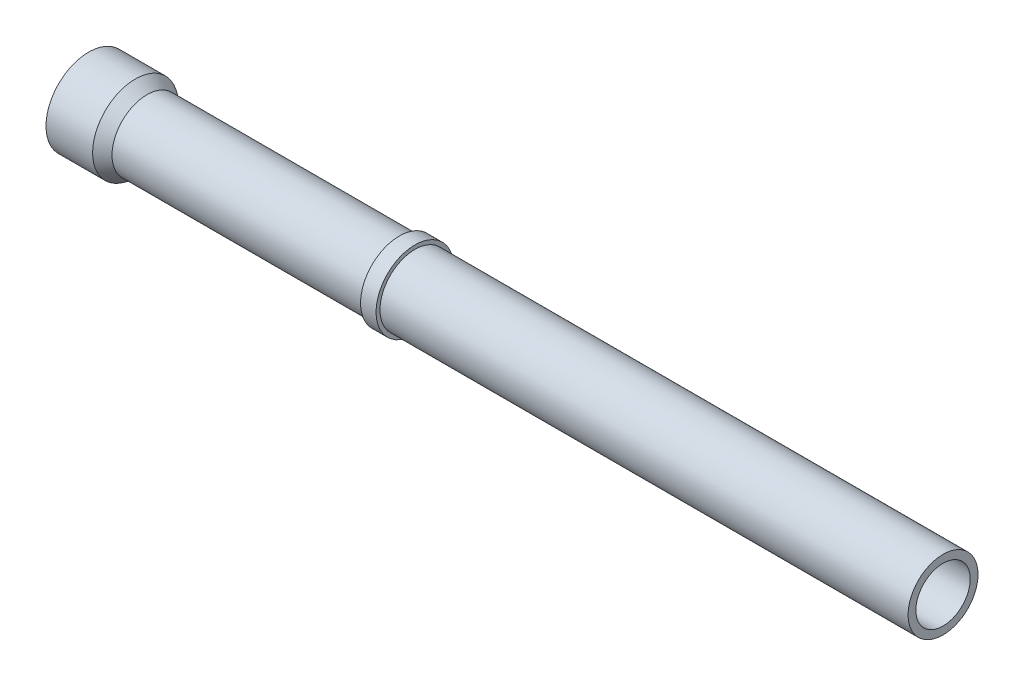
SolidWorks part; units mm, degrees
ref_plane "Front Plane" through (0, 0, 0) normal (0, 0, 1) x (1, 0, 0)
ref_plane "Top Plane" through (0, 0, 0) normal (0, 1, 0) x (1, 0, 0)
ref_plane "Right Plane" through (0, 0, 0) normal (1, 0, 0) x (0, 0, -1)
sketch "Sketch1" plane through (0, 0, 0) normal (1, 0, 0) x (0, 0, -1)
  circle A0 centre (0, 0) radius 14.2875
  circle A1 centre (0, 0) radius 11.1125
  dimension "D1" = 28.575
  dimension "D2" = 3.175
extrude "Boss-Extrude1" add sketch "Sketch1" along normal blind 349.25 contours A0
ref_plane "Plane1" through (127, 0, 0) normal (1, 0, 0) x (0, 0, -1)
sketch "Sketch2" plane through (127, 0, 0) normal (1, 0, 0) x (0, 0, -1)
  circle A0 centre (0, 0) radius 15.875
  circle A1 centre (0, 0) radius 12.6747
  dimension "D1" = 31.75
extrude "Boss-Extrude2" add sketch "Sketch2" along normal blind 6.35
sketch "Sketch3" plane through (0, 0, 0) normal (0, 0, 1) x (1, 0, 0)
  line L0 (0, 12.5317) -> (0, 17.4625)
  line L1 (0, 14.2875) -> (0, -14.2875) construction
  line L2 (0, 17.4625) -> (19.05, 17.4625)
  line L3 (19.05, 17.4625) -> (23.8125, 14.2875)
  line L4 (23.8125, 14.2875) -> (23.8125, 12.5317)
  line L5 (23.8125, 12.5317) -> (0, 12.5317)
  line L6 (0, 12.5317) -> (0, 11.1125)
  line L7 (0, 11.1125) -> (0, -11.1125) construction
  line L8 (127, 14.2875) -> (0, 14.2875) construction
  line L9 (0, 0) -> (21.5, 0)
  dimension "D1" = 0
  dimension "D2" = 19.05
  dimension "D3" = 17.4625
  dimension "D4" = 4.7625
revolve "Revolve1" add sketch "Sketch3" angle 360 about L9
